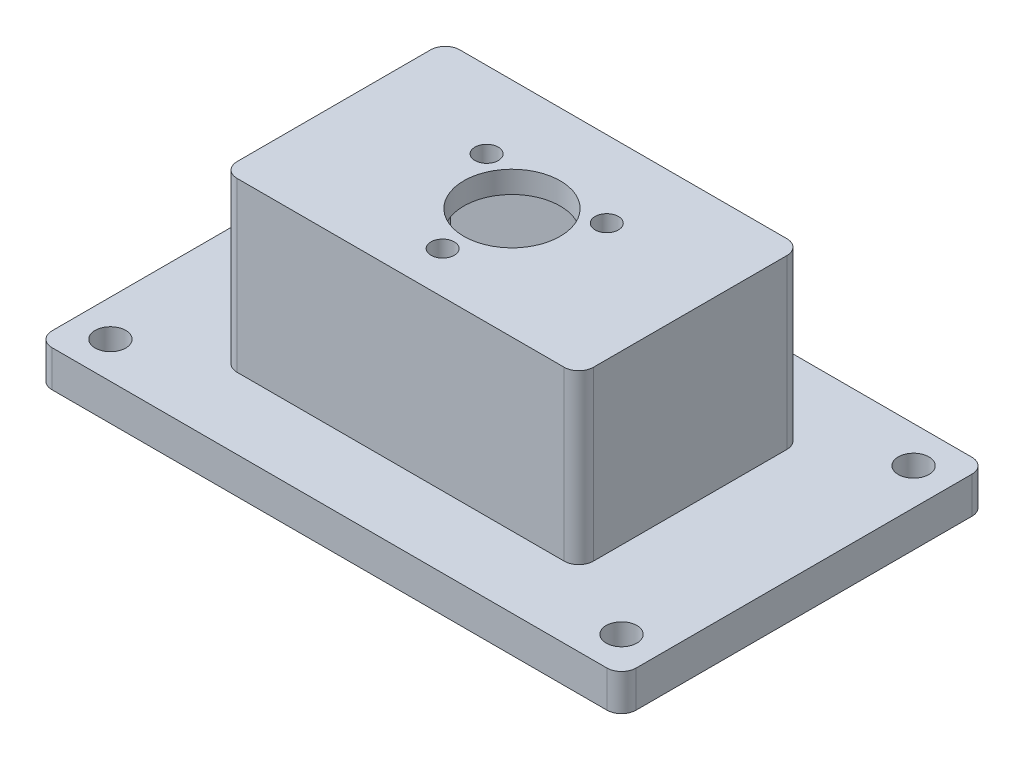
SolidWorks part; units mm, degrees
ref_plane "前视基准面" through (0, 0, 0) normal (0, 0, 1) x (1, 0, 0)
ref_plane "上视基准面" through (0, 0, 0) normal (0, 1, 0) x (1, 0, 0)
ref_plane "右视基准面" through (0, 0, 0) normal (1, 0, 0) x (0, 0, -1)
other "Configuration Table"
sketch "草图1" plane through (0, 0, 0) normal (0, 1, 0) x (1, 0, 0)
  line L0 (-71.5811, 0) -> (51.1966, 0) construction
  line L1 (0, 30.5913) -> (0, -31.8087) construction
  line L3 (-40, -25) -> (40, -25)
  line L4 (-40, -25) -> (-40, 25)
  line L5 (-40, 25) -> (40, 25)
  line L6 (40, -25) -> (40, 25)
  line L7 (-40, -25) -> (40, 25) construction
  line L8 (-40, 25) -> (40, -25) construction
  line L9 (-22.4, -14) -> (22.4, -14)
  line L10 (-22.4, -14) -> (-22.4, 14)
  line L11 (-22.4, 14) -> (22.4, 14)
  line L12 (22.4, -14) -> (22.4, 14)
  line L13 (-22.4, -14) -> (22.4, 14) construction
  line L14 (-22.4, 14) -> (22.4, -14) construction
  circle A0 centre (35, 20) radius 2.1
  circle A2 centre (35, -20) radius 2.1
  circle A3 centre (-35, -20) radius 2.1
  circle A4 centre (-35, 20) radius 2.1
  point P7 (0, 0)
  dimension "D1" = 4.2
  dimension "D4" = 28
  dimension "D2" = 5
  dimension "D3" = 5
  dimension "D5" = 40
  dimension "D6" = 25
extrude "凸台-拉伸1" add sketch "草图1" along normal blind 5
fillet "圆角1" radius 2 4 edges at (-40, 2.5, -25) (-40, 2.5, 25) (40, 2.5, 25) (40, 2.5, -25)
sketch "草图2" plane through (0, 5, 0) normal (0, 1, 0) x (1, 0, 0)
  line L0 (22.4, -14) -> (22.4, 14) construction
  line L1 (-22.4, -14) -> (22.4, -14) construction
  line L2 (-22.4, 14) -> (-22.4, -14) construction
  line L3 (22.4, 14) -> (-22.4, 14) construction
  line L4 (22.4, -14) -> (22.4, 14)
  line L5 (-22.4, -14) -> (22.4, -14)
  line L6 (-22.4, 14) -> (-22.4, -14)
  line L7 (22.4, 14) -> (-22.4, 14)
  line L9 (-24.4, -15.25) -> (24.4, -15.25)
  line L10 (-24.4, -15.25) -> (-24.4, 15.25)
  line L11 (-24.4, 15.25) -> (24.4, 15.25)
  line L12 (24.4, -15.25) -> (24.4, 15.25)
  line L13 (-24.4, -15.25) -> (24.4, 15.25) construction
  line L14 (-24.4, 15.25) -> (24.4, -15.25) construction
  point P3 (0, 0)
  dimension "D1" = 2
extrude "凸台-拉伸2" add sketch "草图2" along normal blind 20
sketch "草图3" plane through (0, 25, 0) normal (0, 1, 0) x (1, 0, 0)
  line L0 (24.4, -15.25) -> (24.4, 15.25) construction
  line L1 (-24.4, -15.25) -> (24.4, -15.25) construction
  line L2 (-24.4, 15.25) -> (-24.4, -15.25) construction
  line L3 (24.4, 15.25) -> (-24.4, 15.25) construction
  line L4 (24.4, -15.25) -> (24.4, 15.25)
  line L5 (-24.4, -15.25) -> (24.4, -15.25)
  line L6 (-24.4, 15.25) -> (-24.4, -15.25)
  line L7 (24.4, 15.25) -> (-24.4, 15.25)
  circle A0 centre (0, 0) radius 6.6
  dimension "D1" = 13.2
extrude "凸台-拉伸3" add sketch "草图3" along normal blind 3
fillet "圆角2" radius 2 4 edges at (-24.4, 16.5, -15.25) (-24.4, 16.5, 15.25) (24.4, 16.5, -15.25) (24.4, 16.5, 15.25)
sketch "草图4" plane through (0, 28, 0) normal (0, 1, 0) x (1, 0, 0)
  line L0 (0, 37.5797) -> (0, -40.2916) construction
  circle A0 centre (0, 0) radius 9.5 construction
  circle A1 centre (0, -9.5) radius 1.6
  circle A2 centre (-8.2272, 4.75) radius 1.6
  circle A3 centre (8.2272, 4.75) radius 1.6
  point P15 (0, 0)
  dimension "D1" = 19
  dimension "D2" = 3.2
  dimension "D3" = 3
extrude "切除-拉伸1" cut sketch "草图4" against normal through all
